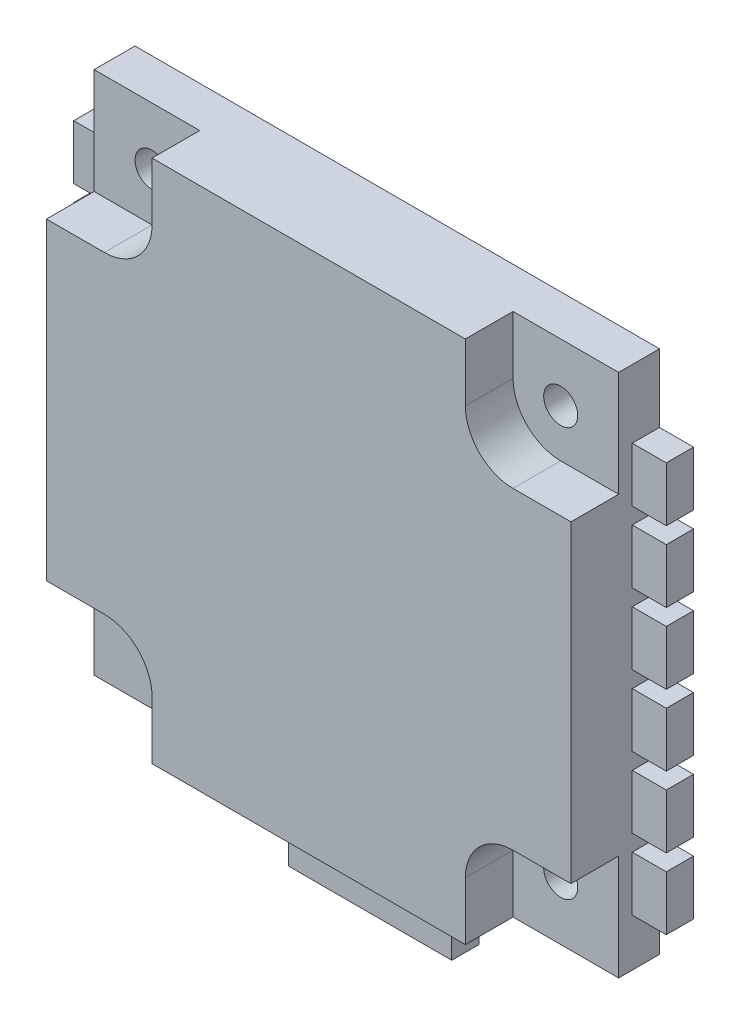
SolidWorks part; units mm, degrees
ref_plane "正面" through (0, 0, 0) normal (0, 0, 1) x (1, 0, 0)
ref_plane "平面" through (0, 0, 0) normal (0, 1, 0) x (1, 0, 0)
ref_plane "右側面" through (0, 0, 0) normal (1, 0, 0) x (0, 0, -1)
sketch "ｽｹｯﾁ1" plane through (0, 0, 0) normal (0, 0, 1) x (1, 0, 0)
  line L1 (-19.25, -19.25) -> (19.25, -19.25)
  line L2 (-19.25, -19.25) -> (-19.25, 19.25)
  line L3 (-19.25, 19.25) -> (19.25, 19.25)
  line L4 (19.25, -19.25) -> (19.25, 19.25)
  line L5 (-19.25, -19.25) -> (19.25, 19.25) construction
  line L6 (-19.25, 19.25) -> (19.25, -19.25) construction
  point P0 (0, 0)
  dimension "D1" = 38.5
  dimension "D2" = 38.5
extrude "ﾎﾞｽ - 押し出し1" add sketch "ｽｹｯﾁ1" along normal blind 6.5
sketch "ｽｹｯﾁ2" plane through (0, 0, 0) normal (0, 0, 1) x (1, 0, 0)
  line L0 (-19.25, 19.25) -> (-19.25, -19.25) construction
  line L1 (-19.25, 14.25) -> (-21.75, 14.25)
  line L2 (-19.25, 14.25) -> (-19.25, 10.25)
  line L3 (-19.25, 10.25) -> (-21.75, 10.25)
  line L4 (-21.75, 14.25) -> (-21.75, 10.25)
  line L5 (-19.25, 10.25) -> (-19.25, 9.05) construction
  line L6 (-19.25, 9.05) -> (-21.75, 9.05)
  line L7 (-19.25, 9.05) -> (-19.25, 5.05)
  line L8 (-19.25, 5.05) -> (-21.75, 5.05)
  line L9 (-21.75, 9.05) -> (-21.75, 5.05)
  line L10 (-19.25, 3.85) -> (-21.75, 3.85)
  line L11 (-19.25, 3.85) -> (-19.25, -0.15)
  line L12 (-19.25, -0.15) -> (-21.75, -0.15)
  line L13 (-21.75, 3.85) -> (-21.75, -0.15)
  line L14 (-19.25, -1.35) -> (-21.75, -1.35)
  line L15 (-19.25, -1.35) -> (-19.25, -5.35)
  line L16 (-19.25, -5.35) -> (-21.75, -5.35)
  line L17 (-21.75, -1.35) -> (-21.75, -5.35)
  line L18 (-19.25, -6.55) -> (-21.75, -6.55)
  line L19 (-19.25, -6.55) -> (-19.25, -10.55)
  line L20 (-19.25, -10.55) -> (-21.75, -10.55)
  line L21 (-21.75, -6.55) -> (-21.75, -10.55)
  line L22 (-19.25, -11.75) -> (-21.75, -11.75)
  line L23 (-19.25, -11.75) -> (-19.25, -15.75)
  line L24 (-19.25, -15.75) -> (-21.75, -15.75)
  line L25 (-21.75, -11.75) -> (-21.75, -15.75)
  line L26 (-19.25, 5.05) -> (-19.25, 3.85) construction
  line L27 (-19.25, -0.15) -> (-19.25, -1.35) construction
  line L28 (-19.25, -5.35) -> (-19.25, -6.55) construction
  line L29 (-19.25, -10.55) -> (-19.25, -11.75) construction
  line L30 (19.25, 19.25) -> (-19.25, 19.25) construction
  line L31 (0, 20.275) -> (0, -20.1218) construction
  line L32 (-19.25, -19.25) -> (19.25, -19.25) construction
  line L33 (-6, -19.25) -> (6, -19.25)
  line L34 (-6, -19.25) -> (-6, -25.25)
  line L35 (-6, -25.25) -> (6, -25.25)
  line L36 (0, -19.25) -> (0, -25.25)
  line L37 (6, -19.25) -> (6, -25.25)
  line L38 (19.25, -15.75) -> (21.75, -15.75)
  line L39 (21.75, -11.75) -> (21.75, -15.75)
  line L40 (19.25, -11.75) -> (21.75, -11.75)
  line L41 (19.25, -11.75) -> (19.25, -15.75)
  line L42 (19.25, -10.55) -> (21.75, -10.55)
  line L43 (21.75, -6.55) -> (21.75, -10.55)
  line L44 (19.25, -6.55) -> (21.75, -6.55)
  line L45 (19.25, -6.55) -> (19.25, -10.55)
  line L46 (19.25, -5.35) -> (21.75, -5.35)
  line L47 (21.75, -1.35) -> (21.75, -5.35)
  line L48 (19.25, -1.35) -> (21.75, -1.35)
  line L49 (19.25, -1.35) -> (19.25, -5.35)
  line L50 (19.25, -0.15) -> (21.75, -0.15)
  line L51 (21.75, 3.85) -> (21.75, -0.15)
  line L52 (19.25, 3.85) -> (21.75, 3.85)
  line L53 (19.25, 3.85) -> (19.25, -0.15)
  line L54 (19.25, 5.05) -> (21.75, 5.05)
  line L55 (21.75, 9.05) -> (21.75, 5.05)
  line L56 (19.25, 9.05) -> (21.75, 9.05)
  line L57 (19.25, 9.05) -> (19.25, 5.05)
  line L58 (19.25, 10.25) -> (21.75, 10.25)
  line L59 (21.75, 14.25) -> (21.75, 10.25)
  line L60 (19.25, 14.25) -> (21.75, 14.25)
  line L61 (19.25, 14.25) -> (19.25, 10.25)
  point P27 (-20.5, 14.25)
  dimension "D1" = 4
  dimension "D2" = 2.5
  dimension "D3" = 30
  dimension "D4" = 5
  dimension "D5" = 6
  dimension "D6" = 6
extrude "ﾎﾞｽ - 押し出し2" add sketch "ｽｹｯﾁ2" along normal blind 2 contours L1 L4 L3 L2 | L6 L9 L8 L7 | L10 L13 L12 L11 | L14 L17 L16 L15 | L18 L21 L20 L19 | L22 L25 L24 L23 | L36 L33 L34 L35 | L37 L33 L36 L35 | L40 L41 L38 L39 | L44 L45 L42 L43 | L52 L53 L50 L51 | L56 L57 L54 L55 | L60 L61 L58 L59 | L47 L46 L49 L48
hole_wizard "M3x0.5 ねじ穴1" positions "ｽｹｯﾁ3" profile "ｽｹｯﾁ4" tap size "M3x0.5" standard "JIS"
sketch "ｽｹｯﾁ3" plane through (0, 0, 6.5) normal (0, 0, 1) x (1, 0, 0)
  point P0 (-15, 15)
  point P11 (15, 15)
  point P12 (15, -15)
  point P13 (-15, -15)
  dimension "D1" = 15
  dimension "D2" = 15
  dimension "D4" = 30
  dimension "D3" = 4
sketch "ｽｹｯﾁ4" plane through (-15, 15, 6.5) normal (1, 0, 0) x (0, -1, 0)
  line L0 (0, 0) -> (0, 8.5)
  line L1 (0, 8.5) -> (1.25, 7.7489)
  line L2 (1.25, 7.7489) -> (1.25, 0)
  line L5 (1.25, 0) -> (0, 0)
  line L10 (0, 8.5) -> (-1.25, 7.7489) construction
  line L11 (0, -6.35) -> (0, 107.95) construction
  dimension "ねじ下穴ﾄﾞﾘﾙ直径" = 2.5
  dimension "ねじ下穴ﾄﾞﾘﾙの深さ" = 8.5
  dimension "ﾄﾞﾘﾙ角度" = 118
sketch "ｽｹｯﾁ5" plane through (0, 0, 6.5) normal (0, 0, 1) x (1, 0, 0)
  line L0 (-11.5, 15) -> (-11.5, 19.25)
  line L1 (19.25, 19.25) -> (-19.25, 19.25) construction
  line L2 (-11.5, 19.25) -> (-19.25, 19.25)
  line L3 (-19.25, 19.25) -> (-19.25, 11.5)
  line L4 (-19.25, 19.25) -> (-19.25, -19.25) construction
  line L5 (-19.25, 11.5) -> (-15, 11.5)
  arc A0 (-15, 11.5) -> (-11.5, 15) centre (-15, 15) ccw
  dimension "D1" = 7
extrude "ｶｯﾄ - 押し出し1" cut sketch "ｽｹｯﾁ5" against normal blind 3.5
sketch "ｽｹｯﾁ6" plane through (0, 0, 0) normal (0, 1, 0) x (1, 0, 0)
  line L0 (0, 0) -> (0, -6.5) construction
  line L1 (19.25, -6.5) -> (-11.5, -6.5) construction
pattern_circular "円形ﾊﾟﾀｰﾝ1" count 4 over 360 about axis through (0, 0, 0) along (0, 0, 1) of "ｶｯﾄ - 押し出し1"
